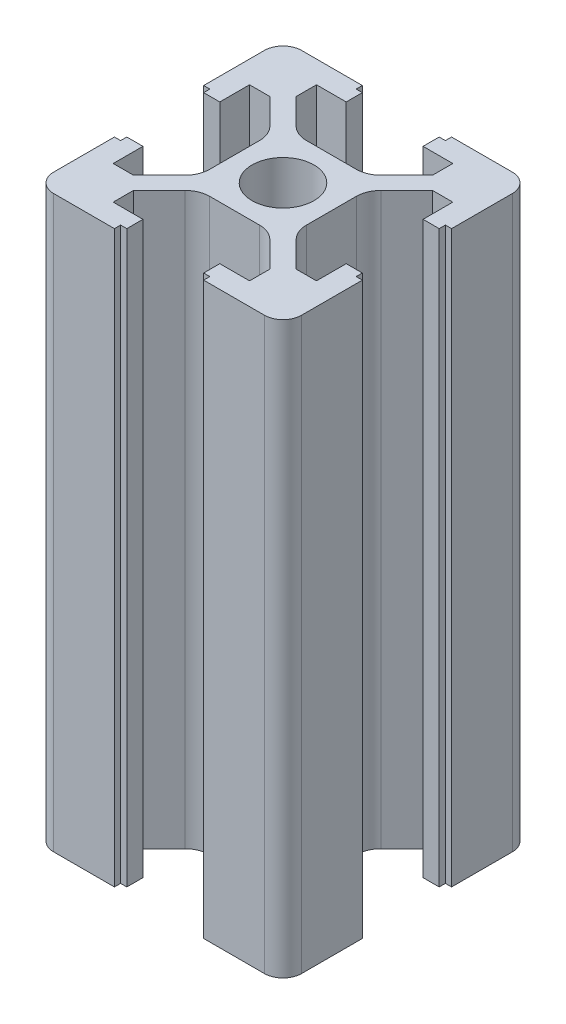
SolidWorks part; units mm, degrees
material "1060 Alloy"
ref_plane "Front Plane" through (0, 0, 0) normal (0, 0, 1) x (1, 0, 0)
ref_plane "Top Plane" through (0, 0, 0) normal (0, 1, 0) x (1, 0, 0)
ref_plane "Right Plane" through (0, 0, 0) normal (1, 0, 0) x (0, 0, -1)
sketch "Sketch1" plane through (0, 0, 0) normal (0, 1, 0) x (1, 0, 0)
  line L1 (8.5, 10) -> (-8.5, 10)
  line L2 (10, 8.5) -> (10, -8.5)
  line L3 (8.5, -10) -> (-8.5, -10)
  line L4 (-10, 8.5) -> (-10, -8.5)
  line L5 (10, 10) -> (-10, -10) construction
  line L6 (10, -10) -> (-10, 10) construction
  arc A0 (-8.5, -10) -> (-10, -8.5) centre (-8.5, -8.5) cw
  arc A1 (10, -8.5) -> (8.5, -10) centre (8.5, -8.5) cw
  arc A2 (8.5, 10) -> (10, 8.5) centre (8.5, 8.5) cw
  arc A3 (-8.5, 10) -> (-10, 8.5) centre (-8.5, 8.5) ccw
  point P0 (0, 0)
  dimension "D3" = 1.5
  dimension "D1" = 20
  dimension "D2" = 20
extrude "Boss-Extrude1" add sketch "Sketch1" along normal blind 46
sketch "Sketch4" plane through (0, 0, 0) normal (0, 1, 0) x (1, 0, 0)
  circle A0 centre (0, 0) radius 2.5
  dimension "D1" = 5
extrude "Cut-Extrude2" cut sketch "Sketch4" along normal through all
sketch "Sketch2" plane through (0, 0, 0) normal (0, -1, 0) x (1, 0, 0)
  line L0 (-3.6, -10) -> (-3.6, -9.5)
  line L1 (8.5, -10) -> (-8.5, -10) construction
  line L2 (-3.6, -9.5) -> (-3.1, -9.5)
  line L3 (-3.1, -9.5) -> (-3.1, -8.2)
  line L4 (-3.1, -8.2) -> (-5.5, -8.2)
  line L5 (-5.5, -8.2) -> (-5.5, -6.5607)
  line L6 (-5.5, -6.5607) -> (-2.8393, -3.9)
  line L7 (-2.8393, -3.9) -> (2.8393, -3.9)
  line L8 (2.8393, -3.9) -> (5.5, -6.5607)
  line L9 (5.5, -6.5607) -> (5.5, -8.2)
  line L10 (5.5, -8.2) -> (3.1, -8.2)
  line L11 (3.1, -8.2) -> (3.1, -9.5)
  line L12 (3.1, -9.5) -> (3.6, -9.5)
  line L13 (3.6, -9.5) -> (3.6, -10)
  line L14 (-5.5, -6.5607) -> (5.5, -6.5607) construction
  line L15 (-3.1, -8.2) -> (3.1, -8.2) construction
  line L16 (3.1, -9.5) -> (-3.1, -9.5) construction
  line L17 (-3.6, -10) -> (3.6, -10)
  line L18 (-9.5607, -9.5607) -> (9.5607, 9.5607) construction
  line L19 (9.5607, -9.5607) -> (-9.5607, 9.5607) construction
  arc A0 (-10, -8.5) -> (-8.5, -10) centre (-8.5, -8.5) ccw construction
  arc A1 (10, 8.5) -> (8.5, 10) centre (8.5, 8.5) ccw construction
  arc A2 (8.5, -10) -> (10, -8.5) centre (8.5, -8.5) ccw construction
  arc A3 (-8.5, 10) -> (-10, 8.5) centre (-8.5, 8.5) ccw construction
  point P5 (0, -3.9)
  point P17 (0, -9.5)
  point P18 (0, -8.2)
  point P20 (0, -6.5607)
  point P21 (0, -10)
  dimension "D1" = 7.2
  dimension "D2" = 6.2
  dimension "D3" = 0.5
  dimension "D4" = 11
  dimension "D5" = 6.1
  dimension "D6" = 1.8
  dimension "D7" = 0.75
extrude "Cut-Extrude1" cut sketch "Sketch2" against normal through all
fillet "Fillet1" radius 2
pattern_circular "CirPattern1" count 4 over 360 about axis through (0, 0, 0) along (0, 1, 0) of "Cut-Extrude1", "Fillet1"
